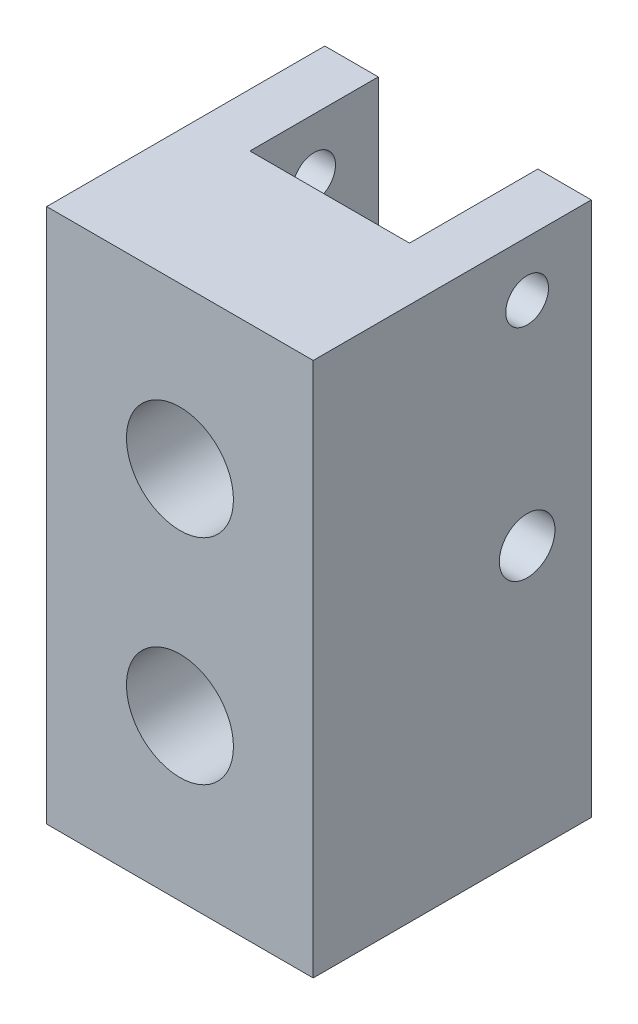
SolidWorks part; units mm, degrees
ref_plane "Front Plane" through (0, 0, 0) normal (0, 0, 1) x (1, 0, 0)
ref_plane "Top Plane" through (0, 0, 0) normal (0, 1, 0) x (1, 0, 0)
ref_plane "Right Plane" through (0, 0, 0) normal (1, 0, 0) x (0, 0, -1)
sketch "Sketch1" plane through (0, 0, 0) normal (0, 1, 0) x (1, 0, 0)
  line L0 (0, 0) -> (0, 33.02)
  line L1 (0, 33.02) -> (6.35, 33.02)
  line L2 (6.35, 33.02) -> (6.35, 17.78)
  line L3 (6.35, 17.78) -> (25.2944, 17.78)
  line L7 (31.6444, 0) -> (0, 0)
  line L8 (15.8222, 0) -> (15.8222, 17.78) construction
  line L9 (31.6444, 33.02) -> (25.2944, 33.02)
  line L10 (25.2944, 33.02) -> (25.2944, 17.78)
  line L11 (31.6444, 0) -> (31.6444, 33.02)
  dimension "D1" = 6.35
  dimension "D2" = 17.78
  dimension "D3" = 33.02
extrude "Boss-Extrude1" add sketch "Sketch1" along normal blind 63.5
sketch "Sketch2" plane through (0, 0, 0) normal (0, 0, 1) x (1, 0, 0)
  line L0 (15.8222, 63.5) -> (15.8222, 0) construction
  line L1 (0, 63.5) -> (31.6444, 63.5) construction
  line L2 (0, 0) -> (31.6444, 0) construction
  circle A0 centre (15.8222, 44.45) radius 6.35
  circle A1 centre (15.8222, 19.05) radius 6.35
  point P8 (15.8222, 31.75)
  dimension "D1" = 25.4
  dimension "D2" = 12.7
extrude "Cut-Extrude1" cut sketch "Sketch2" against normal through all
sketch "Sketch5" plane through (6.35, 0, 0) normal (1, 0, 0) x (0, 0, -1)
  line L0 (17.78, 31.75) -> (33.02, 31.75) construction
  line L1 (17.78, 63.5) -> (17.78, 0) construction
  line L2 (33.02, 63.5) -> (33.02, 0) construction
  line L3 (25.4, 63.5) -> (25.4, 0) construction
  line L4 (17.78, 63.5) -> (33.02, 63.5) construction
  line L5 (17.78, 0) -> (33.02, 0) construction
  circle A0 centre (25.4, 31.75) radius 3.302
  circle A1 centre (25.4, 56.99) radius 2.54
extrude "Cut-Extrude2" cut sketch "Sketch5" against normal through all and the other way through all
